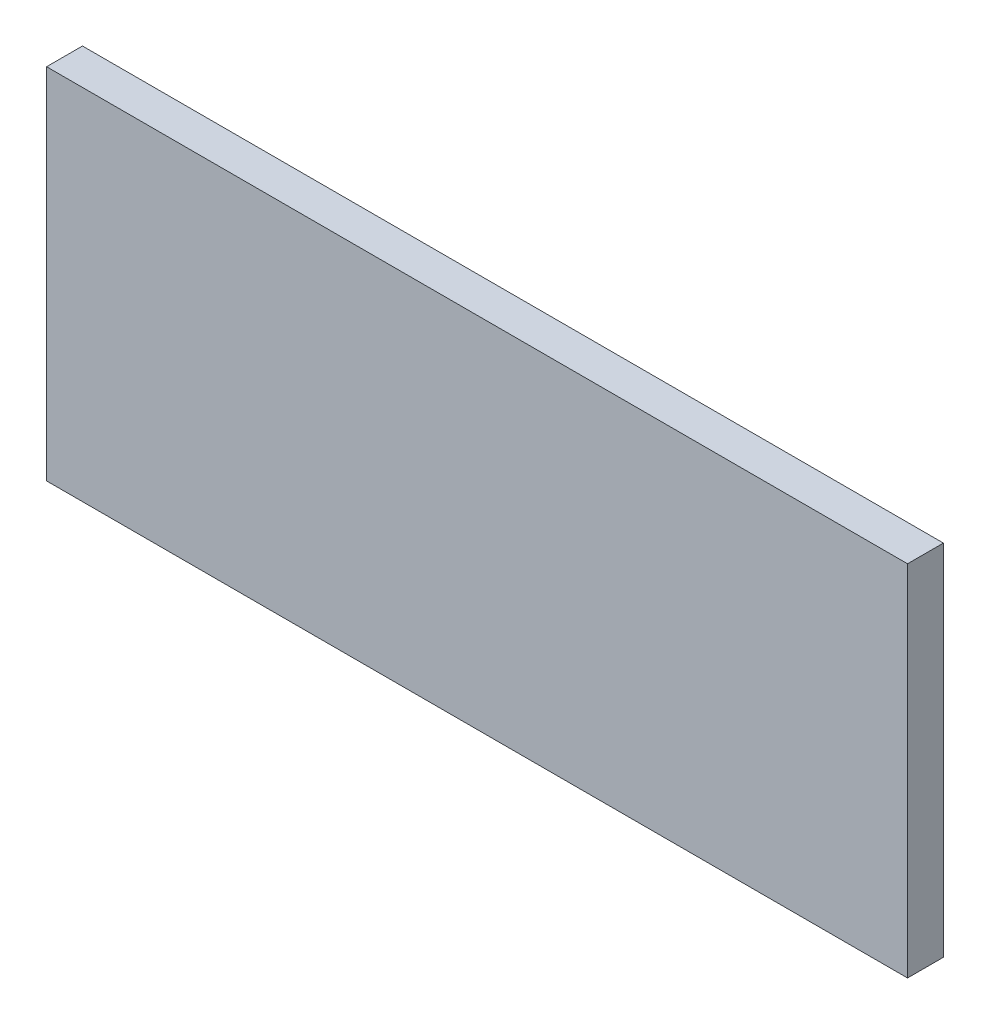
SolidWorks part; units mm, degrees
ref_plane "Front Plane" through (0, 0, 0) normal (0, 0, 1) x (1, 0, 0)
ref_plane "Top Plane" through (0, 0, 0) normal (0, 1, 0) x (1, 0, 0)
ref_plane "Right Plane" through (0, 0, 0) normal (1, 0, 0) x (0, 0, -1)
sketch "Sketch1" plane through (0, 0, 0) normal (0, 0, 1) x (1, 0, 0)
  line L1 (-76.2, -31.75) -> (76.2, -31.75)
  line L2 (-76.2, -31.75) -> (-76.2, 31.75)
  line L3 (-76.2, 31.75) -> (76.2, 31.75)
  line L4 (76.2, -31.75) -> (76.2, 31.75)
  line L5 (-76.2, -31.75) -> (76.2, 31.75) construction
  line L6 (-76.2, 31.75) -> (76.2, -31.75) construction
  point P0 (0, 0)
  dimension "D1" = 152.4
  dimension "D2" = 63.5
extrude "Boss-Extrude1" add sketch "Sketch1" along normal blind 6.35
equation "\"bottom-panel-width\"= 6in"
equation "\"bottom-panel-height\"= 2.5in"
equation "\"material-thickness\"= .25in"
equation "\"D1@Sketch1\"= \"bottom-panel-width\""
equation "\"D2@Sketch1\"=\"bottom-panel-height\""
equation "\"D1@Boss-Extrude1\"=\"material-thickness\""
